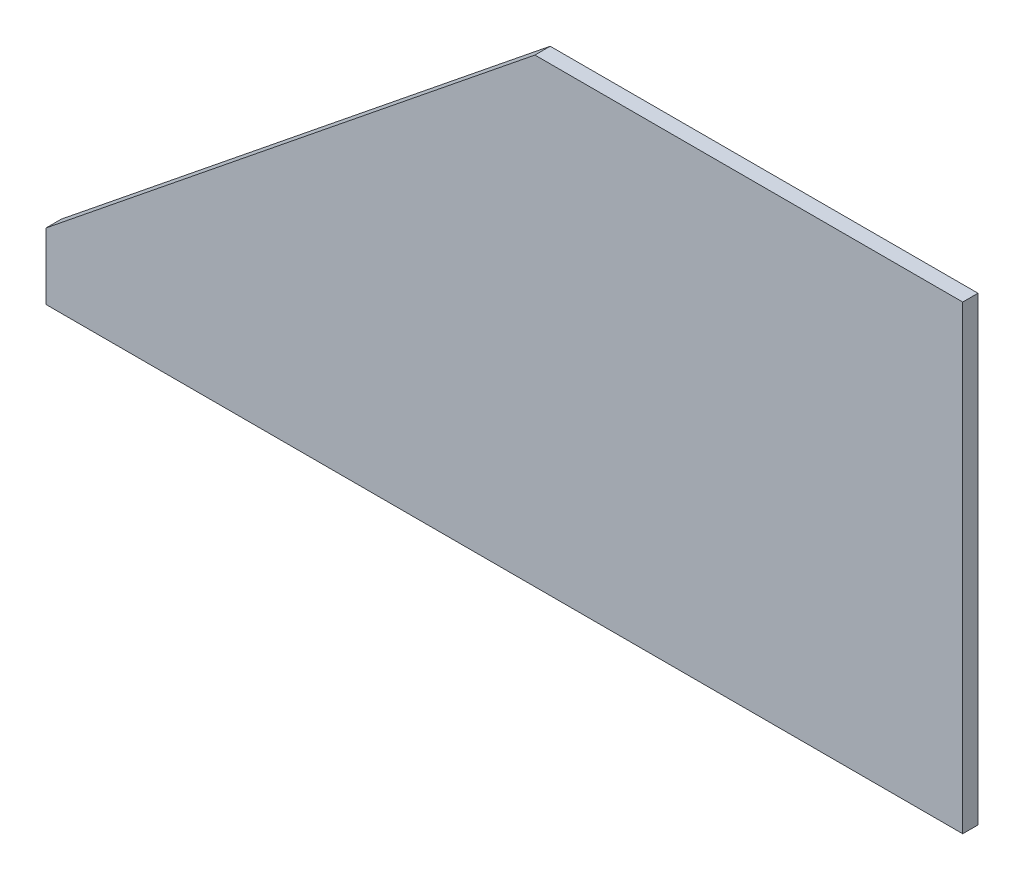
SolidWorks part; units mm, degrees
material "E-Glass Fiber"
ref_plane "Front Plane" through (0, 0, 0) normal (0, 0, 1) x (1, 0, 0)
ref_plane "Top Plane" through (0, 0, 0) normal (0, 1, 0) x (1, 0, 0)
ref_plane "Right Plane" through (0, 0, 0) normal (1, 0, 0) x (0, 0, -1)
sketch "Sketch1" plane through (0, 0, 0) normal (0, 0, 1) x (1, 0, 0)
  line L0 (0, 0) -> (203.2, 163.83)
  line L1 (203.2, 163.83) -> (381, 163.83)
  line L2 (381, 163.83) -> (381, -27.559)
  line L5 (381, -27.559) -> (0, -27.559)
  line L6 (0, -27.559) -> (0, 0)
  point P2 (0, 0)
  point P6 (0, 0)
  point P8 (0, 0)
  dimension "D1" = 163.83
  dimension "D2" = 203.2
  dimension "D3" = 381
  dimension "D4" = 27.559
extrude "Boss-Extrude1" add sketch "Sketch1" along normal blind 6.35
